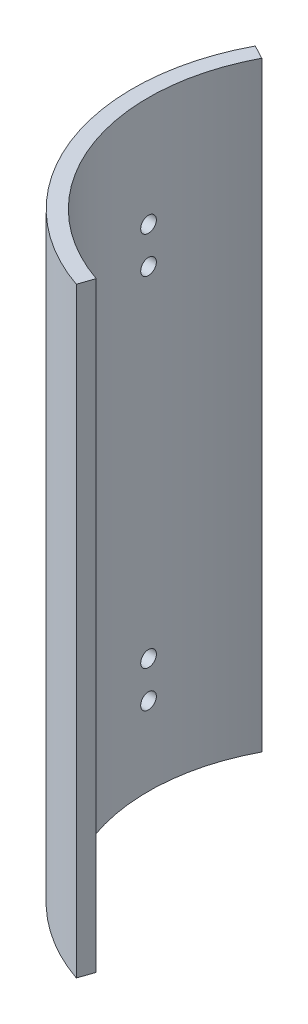
SolidWorks part; units mm, degrees
ref_plane "Plan de face" through (0, 0, 0) normal (0, 0, 1) x (1, 0, 0)
ref_plane "Plan de dessus" through (0, 0, 0) normal (0, 1, 0) x (1, 0, 0)
ref_plane "Plan de droite" through (0, 0, 0) normal (1, 0, 0) x (0, 0, -1)
sketch "Esquisse5" plane through (0, 0, 0) normal (0, 1, 0) x (1, 0, 0)
  line L0 (-11.982, -35.0062) -> (-12.9535, -37.8445)
  line L1 (0, 0) -> (-11.982, -35.0062) construction
  line L2 (0, -38.0423) -> (0, 0) construction
  line L3 (-35.3179, 18.7789) -> (-32.6691, 17.3704)
  arc A0 (-11.982, -35.0062) -> (-32.6691, 17.3704) centre (0, 0) cw
  arc A1 (-12.9535, -37.8445) -> (-35.3179, 18.7789) centre (0, 0) cw
  dimension "D1" = 12.3607
extrude "Extrusion1" add sketch "Esquisse5" along normal blind 115
sketch "Esquisse6" plane through (0, 0, 0) normal (1, 0, 0) x (0, 0, -1)
  line L0 (0, 0) -> (0, 120) construction
  line L1 (17.3704, 115) -> (-35.0062, 115) construction
  line L2 (17.3704, 115) -> (-35.0062, 115) construction
  line L3 (28.5445, 69) -> (17.5, 69)
  line L4 (28.5445, 69) -> (28.5445, 49)
  line L5 (28.5445, 49) -> (17.5, 49)
  line L6 (17.5, 69) -> (17.5, 49)
  circle A0 centre (0, 94) radius 1.5
  circle A1 centre (0, 87) radius 1.5
  circle A3 centre (0, 15) radius 1.5
  circle A4 centre (0, 22) radius 1.5
  dimension "D1" = 72
  dimension "D5" = 17.5
  dimension "D2" = 7
  dimension "D3" = 21
  dimension "D4" = 7
  dimension "D6" = 20
  dimension "D7" = 46
extrude "Extrusion2" cut sketch "Esquisse6" against normal blind 120
